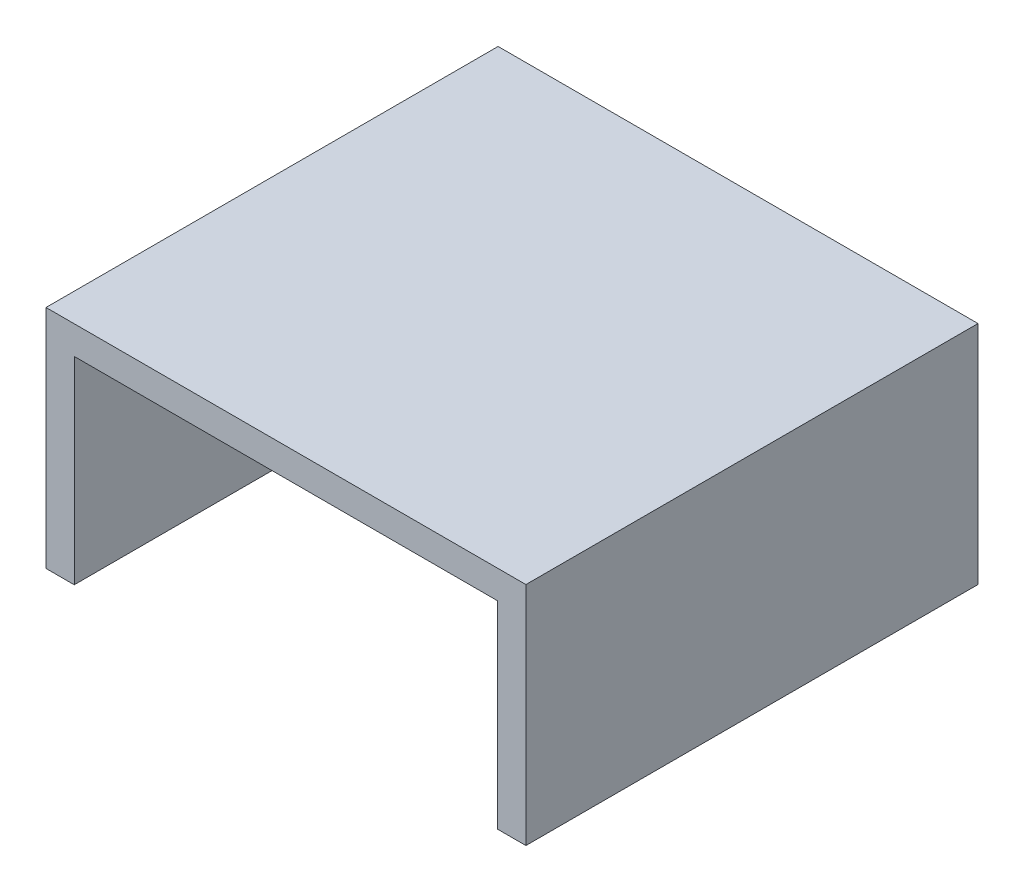
SolidWorks part; units mm, degrees
ref_plane "Front Plane" through (0, 0, 0) normal (0, 0, 1) x (1, 0, 0)
ref_plane "Top Plane" through (0, 0, 0) normal (0, 1, 0) x (1, 0, 0)
ref_plane "Right Plane" through (0, 0, 0) normal (1, 0, 0) x (0, 0, -1)
sketch "Sketch1" plane through (0, 0, 0) normal (0, 0, 1) x (1, 0, 0)
  line L0 (-26.9621, -22.225) -> (-26.9621, 3.175)
  line L1 (-26.9621, 3.175) -> (26.9621, 3.175)
  line L2 (26.9621, 3.175) -> (26.9621, -22.225)
  line L3 (26.9621, -22.225) -> (23.7871, -22.225)
  line L4 (23.7871, -22.225) -> (23.7871, 0)
  line L5 (23.7871, 0) -> (-23.7871, 0)
  line L6 (-23.7871, 0) -> (-23.7871, -22.225)
  line L7 (-23.7871, -22.225) -> (-26.9621, -22.225)
  point P6 (0, 0)
  dimension "D1" = 3.175
  dimension "D2" = 53.9242
  dimension "D3" = 25.4
  dimension "D4" = 3.175
extrude "Boss-Extrude1" add sketch "Sketch1" along normal blind 50.8
